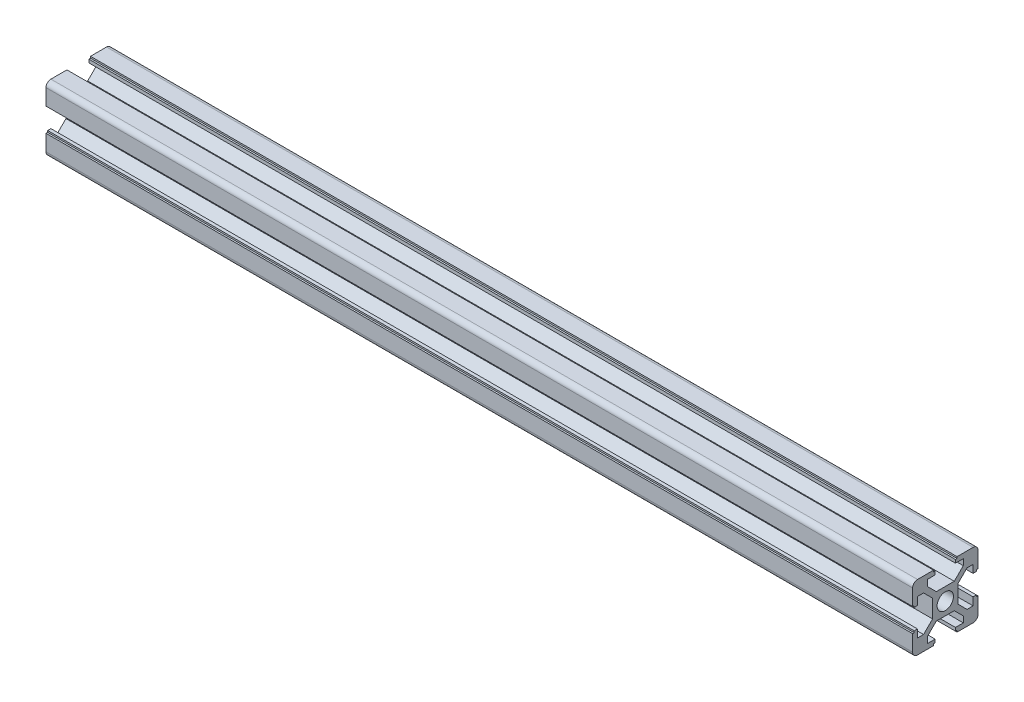
SolidWorks part; units mm, degrees
ref_plane "前视基准面" through (0, 0, 0) normal (0, 0, 1) x (1, 0, 0)
ref_plane "上视基准面" through (0, 0, 0) normal (0, 1, 0) x (1, 0, 0)
ref_plane "右视基准面" through (0, 0, 0) normal (1, 0, 0) x (0, 0, -1)
sketch "草图1" plane through (0, 0, 0) normal (0, 1, 0) x (1, 0, 0)
  line L0 (0, 0) -> (265, 0)
  dimension "D1" = 265
other "铝型材 20 X 20 X R1.5(1)"
ref_plane "基准面1" through (0, 0, 0) normal (1, 0, 0) x (0, 0, -1)
sketch "Sketch1" plane through (0, 0, 0) normal (1, 0, 0) x (0, 0, -1)
  line L0 (-3.6, 10) -> (-3.6, 9.5)
  line L1 (-3.6, 9.5) -> (-3.1, 9.5)
  line L2 (-3.1, 9.5) -> (-3.1, 8.5)
  line L3 (-3.1, 8.5) -> (-5.5, 8.5)
  line L4 (-8.5, -10) -> (-3.6, -10)
  line L5 (-10, -8.5) -> (-10, -3.6)
  line L6 (8.5, 10) -> (3.6, 10)
  line L7 (10, 8.5) -> (10, 3.6)
  line L8 (0, 14.8756) -> (0, 0) construction
  line L9 (0, 0) -> (14.1675, 0) construction
  line L10 (-5.5, 8.5) -> (-5.5, 6.65)
  line L11 (-5.5, 6.65) -> (-2.75, 3.9)
  line L12 (-2.75, 3.9) -> (2.75, 3.9)
  line L13 (5.5, 6.65) -> (2.75, 3.9)
  line L14 (5.5, 8.5) -> (5.5, 6.65)
  line L15 (3.1, 8.5) -> (5.5, 8.5)
  line L16 (3.1, 9.5) -> (3.1, 8.5)
  line L17 (3.6, 9.5) -> (3.1, 9.5)
  line L18 (3.6, 10) -> (3.6, 9.5)
  line L19 (-3.6, 10) -> (-8.5, 10)
  line L20 (10, 3.6) -> (9.5, 3.6)
  line L21 (9.5, 3.6) -> (9.5, 3.1)
  line L22 (9.5, 3.1) -> (8.5, 3.1)
  line L23 (8.5, 3.1) -> (8.5, 5.5)
  line L24 (8.5, 5.5) -> (6.65, 5.5)
  line L25 (6.65, 5.5) -> (3.9, 2.75)
  line L26 (3.9, 2.75) -> (3.9, -2.75)
  line L27 (6.65, -5.5) -> (3.9, -2.75)
  line L28 (8.5, -5.5) -> (6.65, -5.5)
  line L29 (8.5, -3.1) -> (8.5, -5.5)
  line L30 (9.5, -3.1) -> (8.5, -3.1)
  line L31 (9.5, -3.6) -> (9.5, -3.1)
  line L32 (10, -3.6) -> (9.5, -3.6)
  line L33 (3.6, -10) -> (3.6, -9.5)
  line L34 (3.6, -9.5) -> (3.1, -9.5)
  line L35 (3.1, -9.5) -> (3.1, -8.5)
  line L36 (3.1, -8.5) -> (5.5, -8.5)
  line L37 (5.5, -8.5) -> (5.5, -6.65)
  line L38 (5.5, -6.65) -> (2.75, -3.9)
  line L39 (2.75, -3.9) -> (-2.75, -3.9)
  line L40 (-5.5, -6.65) -> (-2.75, -3.9)
  line L41 (-5.5, -8.5) -> (-5.5, -6.65)
  line L42 (-3.1, -8.5) -> (-5.5, -8.5)
  line L43 (-3.1, -9.5) -> (-3.1, -8.5)
  line L44 (-3.6, -9.5) -> (-3.1, -9.5)
  line L45 (-3.6, -10) -> (-3.6, -9.5)
  line L46 (-10, -3.6) -> (-9.5, -3.6)
  line L47 (-9.5, -3.6) -> (-9.5, -3.1)
  line L48 (-9.5, -3.1) -> (-8.5, -3.1)
  line L49 (-8.5, -3.1) -> (-8.5, -5.5)
  line L50 (-8.5, -5.5) -> (-6.65, -5.5)
  line L51 (-6.65, -5.5) -> (-3.9, -2.75)
  line L52 (-3.9, -2.75) -> (-3.9, 2.75)
  line L53 (-6.65, 5.5) -> (-3.9, 2.75)
  line L54 (-8.5, 5.5) -> (-6.65, 5.5)
  line L55 (-8.5, 3.1) -> (-8.5, 5.5)
  line L56 (-9.5, 3.1) -> (-8.5, 3.1)
  line L57 (-9.5, 3.6) -> (-9.5, 3.1)
  line L58 (-10, 3.6) -> (-9.5, 3.6)
  line L59 (3.6, -10) -> (8.5, -10)
  line L60 (-10, 3.6) -> (-10, 8.5)
  line L61 (10, -3.6) -> (10, -8.5)
  circle A0 centre (0, 0) radius 2.5
  arc A1 (-10, 8.5) -> (-8.5, 10) centre (-8.5, 8.5) cw
  arc A2 (10, 8.5) -> (8.5, 10) centre (8.5, 8.5) ccw
  arc A3 (-8.5, -10) -> (-10, -8.5) centre (-8.5, -8.5) cw
  arc A4 (8.5, -10) -> (10, -8.5) centre (8.5, -8.5) ccw
  point P0 (-10, 0)
  point P1 (10, 0)
  point P2 (0, 10)
  point P3 (0, -10)
  point P4 (0, 0)
  point P5 (-10, -10)
  point P6 (10, -10)
  point P7 (10, 10)
  point P8 (-10, 10)
  point P13 (0, 0)
  point P36 (-10, 10)
  point P39 (10, 10)
  dimension "D1" = 11
  dimension "D2" = 20
  dimension "D3" = 6.2
  dimension "D4" = 7.2
  dimension "D5" = 6.1
  dimension "D6" = 5
  dimension "D7" = 1.5
  dimension "D8" = 45
  dimension "D9" = 0.5
  dimension "D10" = 1
  dimension "D11" = 5.5
